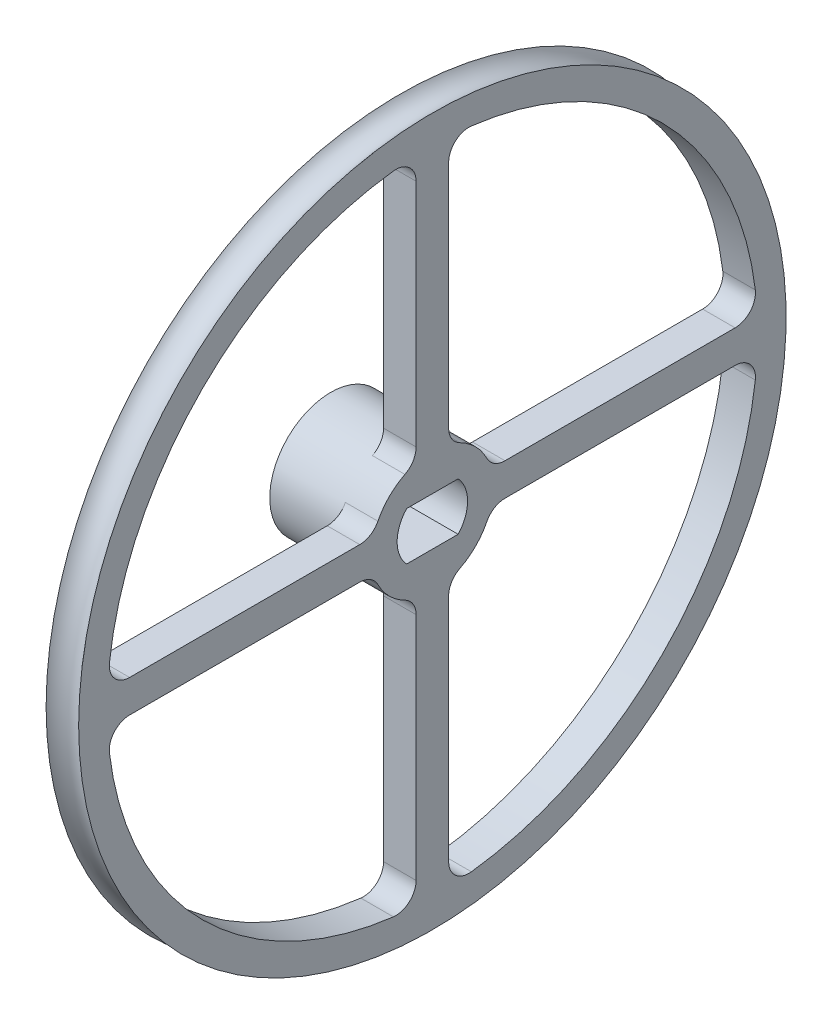
SolidWorks part; units mm, degrees
ref_plane "Front Plane" through (0, 0, 0) normal (0, 0, 1) x (1, 0, 0)
ref_plane "Top Plane" through (0, 0, 0) normal (0, 1, 0) x (1, 0, 0)
ref_plane "Right Plane" through (0, 0, 0) normal (1, 0, 0) x (0, 0, -1)
sketch "Sketch1" plane through (0, 0, 0) normal (0, 0, 1) x (1, 0, 0)
  line L0 (-2.1689, 0) -> (2.1689, 0) construction
  line L1 (-1.27, 25.4) -> (1.27, 25.4)
  line L2 (1.27, 25.4) -> (1.27, 27.6225)
  line L5 (-1.27, 27.6225) -> (-1.27, 25.4)
  arc A0 (1.27, 27.6225) -> (-1.27, 27.6225) centre (0, 28.575) cw
  point P4 (0, 0)
  point P8 (-1.7005, 24.7744)
  point P9 (0, 0)
  point P10 (-1.5526, 28.1133)
  point P12 (0, 0)
  point P13 (0, 0)
  point P14 (1.27, 26.2376)
  dimension "D1" = 1.5875
  dimension "D2" = 57.15
  dimension "D3" = 2.54
  dimension "D4" = 50.8
revolve "Revolve1" add sketch "Sketch1" angle 360 about L0
sketch "Sketch2" plane through (1.27, 0, 0) normal (1, 0, 0) x (0, 0, -1)
  line L0 (-2.0117, 1.875) -> (2.0117, 1.875)
  line L1 (-2.0117, -1.875) -> (2.0117, -1.875)
  arc A0 (-2.0117, 1.875) -> (-2.0117, -1.875) centre (0, 0) ccw
  arc A1 (2.0117, -1.875) -> (2.0117, 1.875) centre (0, 0) ccw
  circle A2 centre (0, 0) radius 4.7625
  dimension "D1" = 5.5
  dimension "D3" = 9.525
  dimension "D2" = 3.75
extrude "Boss-Extrude1" add sketch "Sketch2" against normal blind 7.9375 separate body
sketch "Sketch3" plane through (1.27, 0, 0) normal (1, 0, 0) x (0, 0, -1)
  line L0 (-2.75, 0) -> (-25.4, 0)
  line L1 (2.0117, 1.875) -> (-2.0117, 1.875) construction
  line L2 (0, 1.875) -> (0, 25.4)
  line L3 (2.75, 0) -> (25.4, 0)
  line L4 (0, -1.875) -> (0, -25.4)
  line L5 (-2.0117, -1.875) -> (2.0117, -1.875) construction
  circle A1 centre (0, 0) radius 25.4 construction
  arc A2 (-2.0117, 1.875) -> (-2.0117, -1.875) centre (0, 0) ccw construction
  arc A3 (2.0117, -1.875) -> (2.0117, 1.875) centre (0, 0) ccw construction
  point P2 (0, -1.875)
  point P8 (-2.75, 0)
  point P18 (2.75, 0)
  point P22 (0, 1.875)
extrude "Extrude-Thin1" add sketch "Sketch3" against normal up to surface (2.54 mm away) thin up to face at (-1.27, 0, 25.4) thin type mid plane wall 2.54
fillet "Fillet1" radius 1.5875 16 edges at (0, -1.27, 25.3682) (0, -1.27, 4.59) (0, 1.27, 4.59) (0, 1.27, 25.3682) (0, 25.3682, 1.27) (0, 4.59, 1.27) (0, 25.3682, -1.27) (0, 1.27, -25.3682) (0, 1.27, -4.59) (0, -1.27, -4.59) (0, -1.27, -25.3682) (0, -25.3682, -1.27) (0, -4.59, -1.27) (0, -4.59, 1.27) (0, -25.3682, 1.27) (0, 4.59, -1.27)
